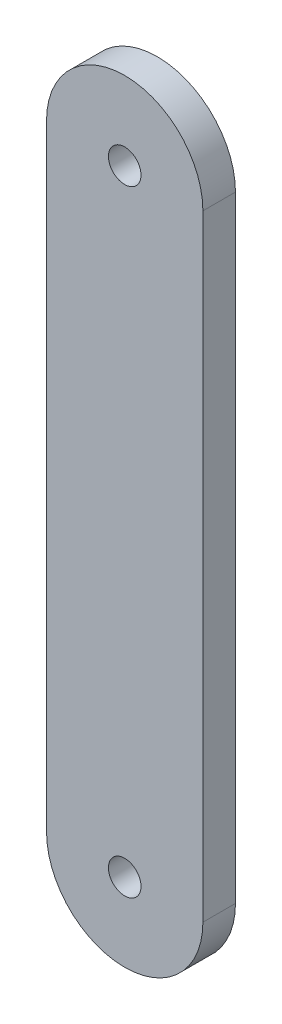
SolidWorks part; units mm, degrees
ref_plane "前视基准面" through (0, 0, 0) normal (0, 0, 1) x (1, 0, 0)
ref_plane "上视基准面" through (0, 0, 0) normal (0, 1, 0) x (1, 0, 0)
ref_plane "右视基准面" through (0, 0, 0) normal (1, 0, 0) x (0, 0, -1)
ref_plane "基准面4" through (0, 0, 5) normal (0, 0, 1) x (1, 0, 0)
sketch "草图1" plane through (0, 0, 5) normal (0, 0, 1) x (1, 0, 0)
  line L0 (12, -47.28) -> (12, 47.28)
  line L1 (-12, 47.28) -> (-12, -47.28)
  circle A0 centre (0, -47.28) radius 2.5
  circle A1 centre (0, 47.28) radius 2.5
  arc A2 (12, 47.28) -> (-12, 47.28) centre (0, 47.28) ccw
  arc A3 (-12, -47.28) -> (12, -47.28) centre (0, -47.28) ccw
  dimension "D1" = 5
  dimension "D2" = 5
  dimension "D3" = 94.56
extrude "凸台-拉伸1" add sketch "草图1" against normal blind 5
